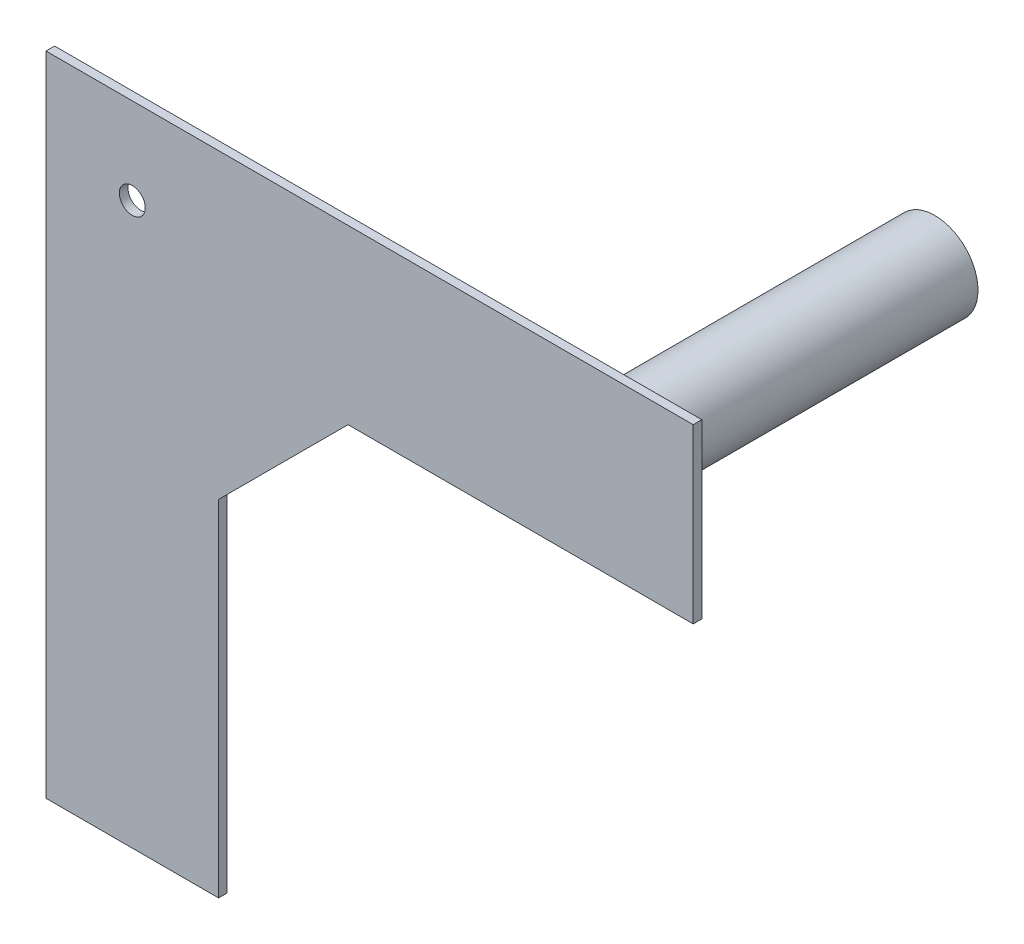
SolidWorks part; units mm, degrees
ref_plane "Front Plane" through (0, 0, 0) normal (0, 0, 1) x (1, 0, 0)
ref_plane "Top Plane" through (0, 0, 0) normal (0, 1, 0) x (1, 0, 0)
ref_plane "Right Plane" through (0, 0, 0) normal (1, 0, 0) x (0, 0, -1)
sketch "Sketch1" plane through (0, 0, 0) normal (0, 0, 1) x (1, 0, 0)
  line L0 (-20, 35) -> (-20, -40)
  line L1 (-20, -40) -> (0, -40)
  line L2 (0, -40) -> (0, 0)
  line L3 (-20, 35) -> (55, 35)
  line L4 (55, 35) -> (55, 15)
  line L5 (55, 15) -> (15, 15)
  line L6 (15, 15) -> (0, 0)
  dimension "D1" = 75
  dimension "D2" = 20
  dimension "D3" = 40
extrude "Boss-Extrude1" add sketch "Sketch1" along normal blind 1
sketch "Sketch4" plane through (0, 0, 1) normal (0, 0, 1) x (1, 0, 0)
  line L0 (-10, -40) -> (-10, 35) construction
  line L1 (-20, -40) -> (0, -40) construction
  line L2 (55, 35) -> (-20, 35) construction
  line L3 (43.821, 35) -> (43.821, 15) construction
  line L4 (15, 15) -> (55, 15) construction
  circle A0 centre (-10, 25.0001) radius 1.5
  point P6 (-10, 25.0001)
  dimension "D1" = 3
extrude "Cut-Extrude5" cut sketch "Sketch4" against normal blind 1
sketch "Sketch5" plane through (0, 0, 1) normal (0, 0, 1) x (1, 0, 0)
  line L0 (43.007, 35) -> (43.007, 15) construction
  line L1 (55, 35) -> (-20, 35) construction
  line L2 (15, 15) -> (55, 15) construction
  circle A0 centre (43.007, 25) radius 5
  dimension "D1" = 10
extrude "Boss-Extrude2" add sketch "Sketch5" against normal blind 40
